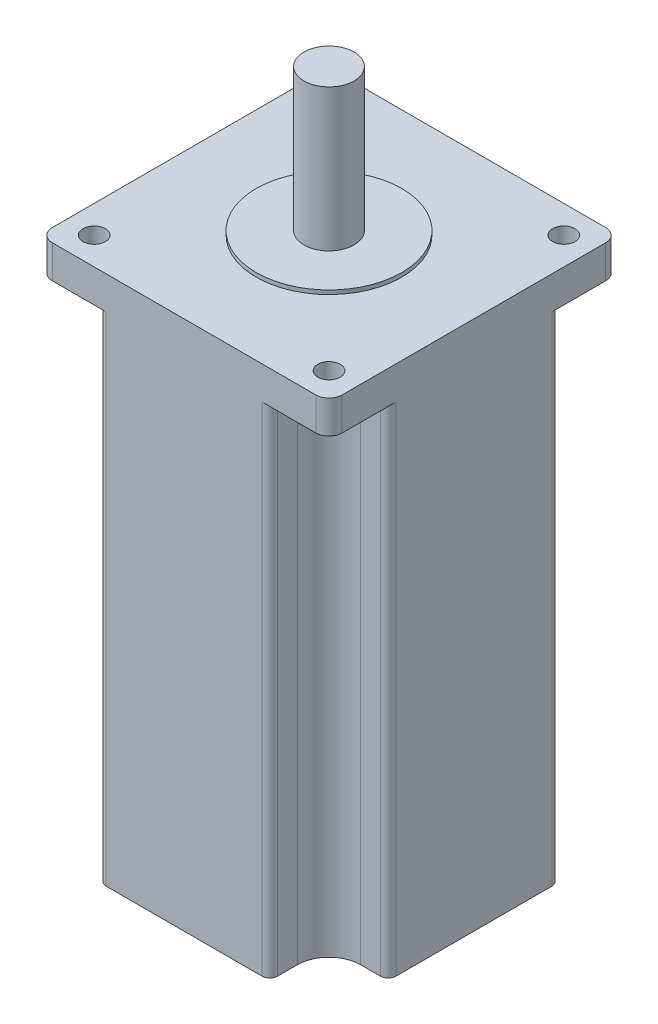
SolidWorks part; units mm, degrees
ref_plane "Front Plane" through (0, 0, 0) normal (0, 0, 1) x (1, 0, 0)
ref_plane "Top Plane" through (0, 0, 0) normal (0, 1, 0) x (1, 0, 0)
ref_plane "Right Plane" through (0, 0, 0) normal (1, 0, 0) x (0, 0, -1)
sketch "Sketch1" plane through (0, 0, 0) normal (0, 1, 0) x (1, 0, 0)
  line L1 (-44.5, -44.5) -> (44.5, -44.5) construction
  line L2 (-44.5, -44.5) -> (-44.5, 44.5) construction
  line L3 (-44.5, 44.5) -> (44.5, 44.5) construction
  line L4 (44.5, -44.5) -> (44.5, 44.5) construction
  line L5 (-44.5, -44.5) -> (44.5, 44.5) construction
  line L6 (-44.5, 44.5) -> (44.5, -44.5) construction
  line L7 (-54.93, -54.93) -> (54.93, -54.93)
  line L8 (-54.93, -54.93) -> (-54.93, 54.93)
  line L9 (-54.93, 54.93) -> (54.93, 54.93)
  line L10 (54.93, -54.93) -> (54.93, 54.93)
  line L11 (-54.93, -54.93) -> (54.93, 54.93) construction
  line L12 (-54.93, 54.93) -> (54.93, -54.93) construction
  circle A0 centre (-44.5, 44.5) radius 4.25
  circle A1 centre (44.5, 44.5) radius 4.25
  circle A2 centre (44.5, -44.5) radius 4.25
  circle A3 centre (-44.5, -44.5) radius 4.25
  point P0 (0, 0)
  point P10 (0, 0)
  dimension "D1" = 8.5
  dimension "D2" = 89
  dimension "D4" = 109.86
extrude "Boss-Extrude1" add sketch "Sketch1" against normal blind 201
fillet "Fillet1" radius 5 4 edges at (-54.93, -100.5, -54.93) (54.93, -100.5, -54.93) (54.93, -100.5, 54.93) (-54.93, -100.5, 54.93)
sketch "Sketch2" plane through (0, 0, 0) normal (0, 1, 0) x (1, 0, 0)
  circle A0 centre (0, 0) radius 27.6
  dimension "D1" = 55.2
extrude "Boss-Extrude2" add sketch "Sketch2" along normal blind 1.52
sketch "Sketch3" plane through (0, 0, 0) normal (0, 1, 0) x (1, 0, 0)
  circle A0 centre (0, 0) radius 9.5
  dimension "D1" = 19
extrude "Boss-Extrude3" add sketch "Sketch3" along normal blind 55.37
sketch "Sketch5" plane through (0, 0, 0) normal (0, 1, 0) x (1, 0, 0)
  line L0 (-44.5, 32.5) -> (-57.5793, 32.5)
  line L1 (-57.5793, 32.5) -> (-57.5793, 62.3565)
  line L2 (-57.5793, 62.3565) -> (-32.5, 61.8616)
  line L3 (-32.5, 61.8616) -> (-32.5, 44.5)
  line L4 (62.3565, 57.5793) -> (61.8616, 32.5)
  line L5 (32.5, 57.5793) -> (62.3565, 57.5793)
  line L6 (61.8616, 32.5) -> (44.5, 32.5)
  line L7 (32.5, 44.5) -> (32.5, 57.5793)
  line L8 (57.5793, -62.3565) -> (32.5, -61.8616)
  line L9 (57.5793, -32.5) -> (57.5793, -62.3565)
  line L10 (32.5, -61.8616) -> (32.5, -44.5)
  line L11 (44.5, -32.5) -> (57.5793, -32.5)
  line L12 (-62.3565, -57.5793) -> (-61.8616, -32.5)
  line L13 (-32.5, -57.5793) -> (-62.3565, -57.5793)
  line L14 (-61.8616, -32.5) -> (-44.5, -32.5)
  line L15 (-32.5, -44.5) -> (-32.5, -57.5793)
  arc A0 (-44.5, 32.5) -> (-32.5, 44.5) centre (-44.5, 44.5) ccw
  arc A1 (32.5, 44.5) -> (44.5, 32.5) centre (44.5, 44.5) ccw
  arc A2 (44.5, -32.5) -> (32.5, -44.5) centre (44.5, -44.5) ccw
  arc A3 (-32.5, -44.5) -> (-44.5, -32.5) centre (-44.5, -44.5) ccw
  point P28 (0, 0)
  dimension "D1" = 12
  dimension "D2" = 4
extrude "Cut-Extrude1" cut sketch "Sketch5" against normal blind 205.37 from offset 12.5 offset against normal yes
fillet "Fillet2" radius 3 8 edges at (-54.93, -106.75, -32.5) (-54.93, -106.75, 32.5) (-32.5, -106.75, 54.93) (32.5, -106.75, 54.93) (54.93, -106.75, 32.5) (54.93, -106.75, -32.5) (32.5, -106.75, -54.93) (-32.5, -106.75, -54.93)
